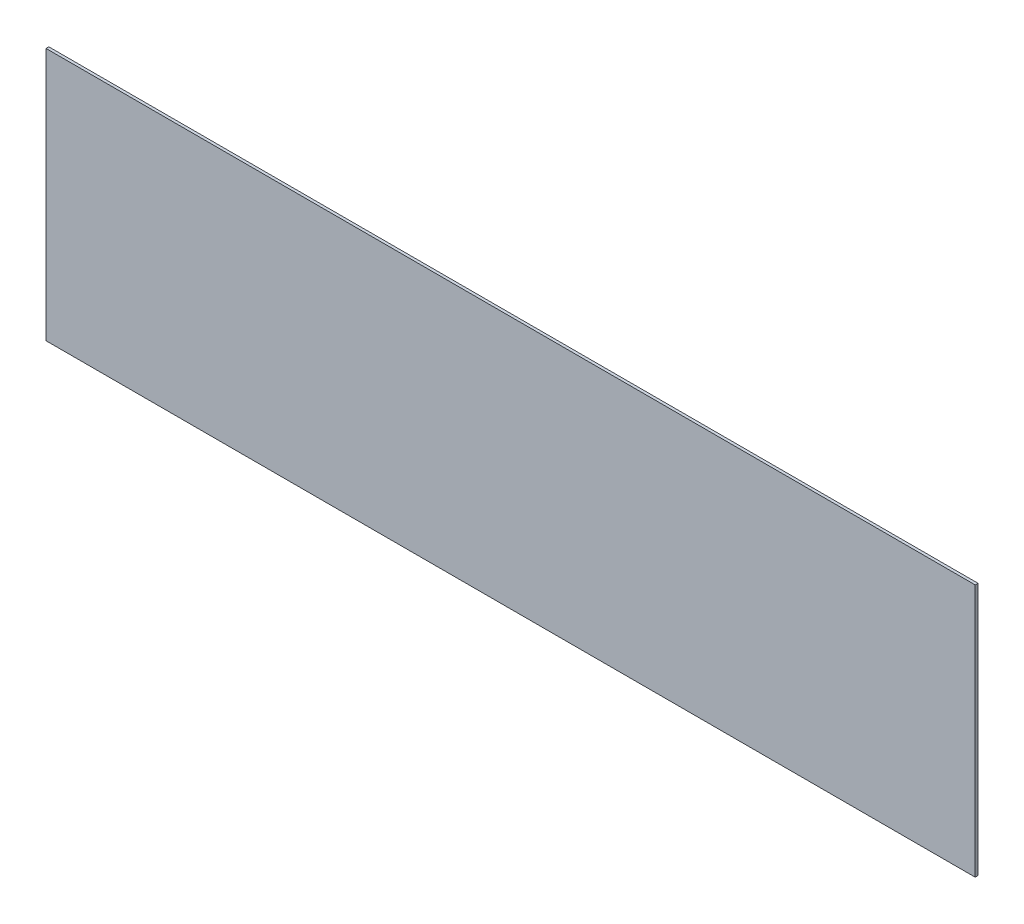
SolidWorks part; units mm, degrees
ref_plane "Front Plane" through (0, 0, 0) normal (0, 0, 1) x (1, 0, 0)
ref_plane "Top Plane" through (0, 0, 0) normal (0, 1, 0) x (1, 0, 0)
ref_plane "Right Plane" through (0, 0, 0) normal (1, 0, 0) x (0, 0, -1)
sketch "Sketch1" plane through (0, 0, 0) normal (0, 0, 1) x (1, 0, 0)
  line L1 (-495.5, -135) -> (495.5, -135)
  line L2 (-495.5, -135) -> (-495.5, 135)
  line L3 (-495.5, 135) -> (495.5, 135)
  line L4 (495.5, -135) -> (495.5, 135)
  line L5 (-495.5, -135) -> (495.5, 135) construction
  line L6 (-495.5, 135) -> (495.5, -135) construction
  point P0 (0, 0)
  dimension "D1" = 270
  dimension "D2" = 991
extrude "Boss-Extrude1" add sketch "Sketch1" along normal blind 3
